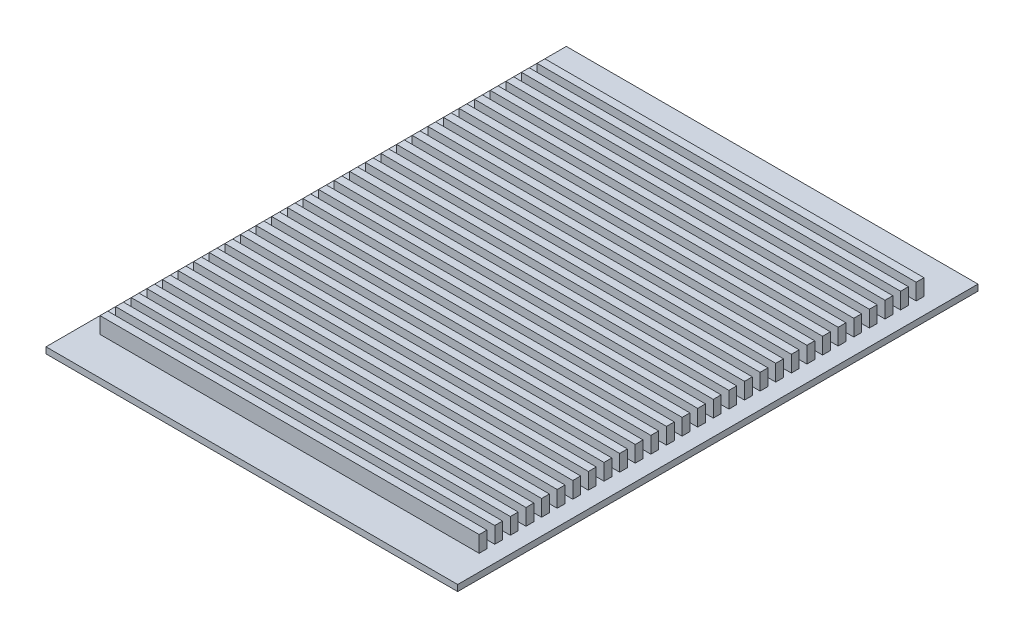
SolidWorks part; units mm, degrees
ref_plane "Front Plane" through (0, 0, 0) normal (0, 0, 1) x (1, 0, 0)
ref_plane "Top Plane" through (0, 0, 0) normal (0, 1, 0) x (1, 0, 0)
ref_plane "Right Plane" through (0, 0, 0) normal (1, 0, 0) x (0, 0, -1)
sketch "Sketch1" plane through (0, 0, 0) normal (0, 1, 0) x (1, 0, 0)
  line L1 (0, 0) -> (160.782, 0)
  line L2 (0, 0) -> (0, 203.2)
  line L3 (0, 203.2) -> (160.782, 203.2)
  line L4 (160.782, 0) -> (160.782, 203.2)
  dimension "D1" = 160.782
  dimension "D2" = 203.2
extrude "Boss-Extrude1" add sketch "Sketch1" along normal blind 2.413
sketch "Sketch2" plane through (0, 2.413, 0) normal (0, 1, 0) x (1, 0, 0)
  line L0 (0, 203.2) -> (0, 0) construction
  line L1 (6.35, 185.42) -> (154.432, 185.42) construction
  line L2 (6.35, 185.42) -> (6.35, 182.372) construction
  line L3 (6.35, 182.372) -> (154.432, 182.372) construction
  line L4 (154.432, 185.42) -> (154.432, 182.372) construction
  line L5 (160.782, 203.2) -> (0, 203.2) construction
  line L6 (6.35, 179.324) -> (6.35, 176.276) construction
  line L7 (6.35, 179.324) -> (154.432, 179.324) construction
  line L8 (154.432, 179.324) -> (154.432, 176.276) construction
  line L9 (6.35, 176.276) -> (154.432, 176.276) construction
  line L10 (6.35, 173.228) -> (6.35, 170.18) construction
  line L11 (6.35, 173.228) -> (154.432, 173.228) construction
  line L12 (154.432, 173.228) -> (154.432, 170.18) construction
  line L13 (6.35, 170.18) -> (154.432, 170.18) construction
  line L14 (6.35, 167.132) -> (6.35, 164.084) construction
  line L15 (6.35, 167.132) -> (154.432, 167.132) construction
  line L16 (154.432, 167.132) -> (154.432, 164.084) construction
  line L17 (6.35, 164.084) -> (154.432, 164.084) construction
  line L18 (6.35, 161.036) -> (6.35, 157.988) construction
  line L19 (6.35, 161.036) -> (154.432, 161.036) construction
  line L20 (154.432, 161.036) -> (154.432, 157.988) construction
  line L21 (6.35, 157.988) -> (154.432, 157.988) construction
  line L22 (6.35, 154.94) -> (6.35, 151.892) construction
  line L23 (6.35, 154.94) -> (154.432, 154.94) construction
  line L24 (154.432, 154.94) -> (154.432, 151.892) construction
  line L25 (6.35, 151.892) -> (154.432, 151.892) construction
  line L26 (6.35, 148.844) -> (6.35, 145.796) construction
  line L27 (6.35, 148.844) -> (154.432, 148.844) construction
  line L28 (154.432, 148.844) -> (154.432, 145.796) construction
  line L29 (6.35, 145.796) -> (154.432, 145.796) construction
  line L30 (6.35, 142.748) -> (6.35, 139.7) construction
  line L31 (6.35, 142.748) -> (154.432, 142.748) construction
  line L32 (154.432, 142.748) -> (154.432, 139.7) construction
  line L33 (6.35, 139.7) -> (154.432, 139.7) construction
  line L34 (6.35, 136.652) -> (6.35, 133.604) construction
  line L35 (6.35, 136.652) -> (154.432, 136.652) construction
  line L36 (154.432, 136.652) -> (154.432, 133.604) construction
  line L37 (6.35, 133.604) -> (154.432, 133.604) construction
  line L38 (6.35, 130.556) -> (6.35, 127.508) construction
  line L39 (6.35, 130.556) -> (154.432, 130.556) construction
  line L40 (154.432, 130.556) -> (154.432, 127.508) construction
  line L41 (6.35, 127.508) -> (154.432, 127.508) construction
  line L42 (6.35, 124.46) -> (6.35, 121.412) construction
  line L43 (6.35, 124.46) -> (154.432, 124.46) construction
  line L44 (154.432, 124.46) -> (154.432, 121.412) construction
  line L45 (6.35, 121.412) -> (154.432, 121.412) construction
  line L46 (6.35, 118.364) -> (6.35, 115.316) construction
  line L47 (6.35, 118.364) -> (154.432, 118.364) construction
  line L48 (154.432, 118.364) -> (154.432, 115.316) construction
  line L49 (6.35, 115.316) -> (154.432, 115.316) construction
  line L50 (6.35, 112.268) -> (6.35, 109.22) construction
  line L51 (6.35, 112.268) -> (154.432, 112.268) construction
  line L52 (154.432, 112.268) -> (154.432, 109.22) construction
  line L53 (6.35, 109.22) -> (154.432, 109.22) construction
  line L54 (6.35, 106.172) -> (6.35, 103.124) construction
  line L55 (6.35, 106.172) -> (154.432, 106.172) construction
  line L56 (154.432, 106.172) -> (154.432, 103.124) construction
  line L57 (6.35, 103.124) -> (154.432, 103.124) construction
  line L58 (6.35, 100.076) -> (6.35, 97.028) construction
  line L59 (6.35, 100.076) -> (154.432, 100.076) construction
  line L60 (154.432, 100.076) -> (154.432, 97.028) construction
  line L61 (6.35, 97.028) -> (154.432, 97.028) construction
  line L62 (6.35, 93.98) -> (6.35, 90.932) construction
  line L63 (6.35, 93.98) -> (154.432, 93.98) construction
  line L64 (154.432, 93.98) -> (154.432, 90.932) construction
  line L65 (6.35, 90.932) -> (154.432, 90.932) construction
  line L66 (6.35, 87.884) -> (6.35, 84.836) construction
  line L67 (6.35, 87.884) -> (154.432, 87.884) construction
  line L68 (154.432, 87.884) -> (154.432, 84.836) construction
  line L69 (6.35, 84.836) -> (154.432, 84.836) construction
  line L70 (6.35, 81.788) -> (6.35, 78.74) construction
  line L71 (6.35, 81.788) -> (154.432, 81.788) construction
  line L72 (154.432, 81.788) -> (154.432, 78.74) construction
  line L73 (6.35, 78.74) -> (154.432, 78.74) construction
  line L74 (6.35, 75.692) -> (6.35, 72.644) construction
  line L75 (6.35, 75.692) -> (154.432, 75.692) construction
  line L76 (154.432, 75.692) -> (154.432, 72.644) construction
  line L77 (6.35, 72.644) -> (154.432, 72.644) construction
  line L78 (6.35, 69.596) -> (6.35, 66.548) construction
  line L79 (6.35, 69.596) -> (154.432, 69.596) construction
  line L80 (154.432, 69.596) -> (154.432, 66.548) construction
  line L81 (6.35, 66.548) -> (154.432, 66.548) construction
  line L82 (6.35, 63.5) -> (6.35, 60.452) construction
  line L83 (6.35, 63.5) -> (154.432, 63.5) construction
  line L84 (154.432, 63.5) -> (154.432, 60.452) construction
  line L85 (6.35, 60.452) -> (154.432, 60.452) construction
  line L86 (6.35, 57.404) -> (6.35, 54.356) construction
  line L87 (6.35, 57.404) -> (154.432, 57.404) construction
  line L88 (154.432, 57.404) -> (154.432, 54.356) construction
  line L89 (6.35, 54.356) -> (154.432, 54.356) construction
  line L90 (6.35, 51.308) -> (6.35, 48.26) construction
  line L91 (6.35, 51.308) -> (154.432, 51.308) construction
  line L92 (154.432, 51.308) -> (154.432, 48.26) construction
  line L93 (6.35, 48.26) -> (154.432, 48.26) construction
  line L94 (6.35, 45.212) -> (6.35, 42.164) construction
  line L95 (6.35, 45.212) -> (154.432, 45.212) construction
  line L96 (154.432, 45.212) -> (154.432, 42.164) construction
  line L97 (6.35, 42.164) -> (154.432, 42.164) construction
  line L98 (6.35, 39.116) -> (6.35, 36.068) construction
  line L99 (6.35, 39.116) -> (154.432, 39.116) construction
  line L100 (154.432, 39.116) -> (154.432, 36.068) construction
  line L101 (6.35, 36.068) -> (154.432, 36.068) construction
  line L102 (6.35, 33.02) -> (6.35, 29.972) construction
  line L103 (6.35, 33.02) -> (154.432, 33.02) construction
  line L104 (154.432, 33.02) -> (154.432, 29.972) construction
  line L105 (6.35, 29.972) -> (154.432, 29.972) construction
  line L106 (6.35, 26.924) -> (6.35, 23.876) construction
  line L107 (6.35, 26.924) -> (154.432, 26.924) construction
  line L108 (154.432, 26.924) -> (154.432, 23.876) construction
  line L109 (6.35, 23.876) -> (154.432, 23.876) construction
  line L110 (6.35, 20.828) -> (6.35, 17.78) construction
  line L111 (6.35, 20.828) -> (154.432, 20.828) construction
  line L112 (154.432, 20.828) -> (154.432, 17.78) construction
  line L113 (6.35, 17.78) -> (154.432, 17.78) construction
  line L114 (6.35, 185.42) -> (6.35, 17.78) construction
  line L115 (6.35, 179.324) -> (6.35, 182.372)
  line L116 (6.35, 185.42) -> (154.432, 185.42)
  line L117 (6.35, 185.42) -> (6.35, 188.468)
  line L118 (6.35, 188.468) -> (154.432, 188.468)
  line L119 (154.432, 185.42) -> (154.432, 188.468)
  line L120 (6.35, 179.324) -> (154.432, 179.324)
  line L121 (154.432, 179.324) -> (154.432, 182.372)
  line L122 (6.35, 182.372) -> (154.432, 182.372)
  line L123 (6.35, 173.228) -> (6.35, 176.276)
  line L124 (6.35, 173.228) -> (154.432, 173.228)
  line L125 (154.432, 173.228) -> (154.432, 176.276)
  line L126 (6.35, 176.276) -> (154.432, 176.276)
  line L127 (6.35, 167.132) -> (6.35, 170.18)
  line L128 (6.35, 167.132) -> (154.432, 167.132)
  line L129 (154.432, 167.132) -> (154.432, 170.18)
  line L130 (6.35, 170.18) -> (154.432, 170.18)
  line L131 (6.35, 161.036) -> (6.35, 164.084)
  line L132 (6.35, 161.036) -> (154.432, 161.036)
  line L133 (154.432, 161.036) -> (154.432, 164.084)
  line L134 (6.35, 164.084) -> (154.432, 164.084)
  line L135 (6.35, 154.94) -> (6.35, 157.988)
  line L136 (6.35, 154.94) -> (154.432, 154.94)
  line L137 (154.432, 154.94) -> (154.432, 157.988)
  line L138 (6.35, 157.988) -> (154.432, 157.988)
  line L139 (6.35, 148.844) -> (6.35, 151.892)
  line L140 (6.35, 148.844) -> (154.432, 148.844)
  line L141 (154.432, 148.844) -> (154.432, 151.892)
  line L142 (6.35, 151.892) -> (154.432, 151.892)
  line L143 (6.35, 142.748) -> (6.35, 145.796)
  line L144 (6.35, 142.748) -> (154.432, 142.748)
  line L145 (154.432, 142.748) -> (154.432, 145.796)
  line L146 (6.35, 145.796) -> (154.432, 145.796)
  line L147 (6.35, 136.652) -> (6.35, 139.7)
  line L148 (6.35, 136.652) -> (154.432, 136.652)
  line L149 (154.432, 136.652) -> (154.432, 139.7)
  line L150 (6.35, 139.7) -> (154.432, 139.7)
  line L151 (6.35, 130.556) -> (6.35, 133.604)
  line L152 (6.35, 130.556) -> (154.432, 130.556)
  line L153 (154.432, 130.556) -> (154.432, 133.604)
  line L154 (6.35, 133.604) -> (154.432, 133.604)
  line L155 (6.35, 124.46) -> (6.35, 127.508)
  line L156 (6.35, 124.46) -> (154.432, 124.46)
  line L157 (154.432, 124.46) -> (154.432, 127.508)
  line L158 (6.35, 127.508) -> (154.432, 127.508)
  line L159 (6.35, 118.364) -> (6.35, 121.412)
  line L160 (6.35, 118.364) -> (154.432, 118.364)
  line L161 (154.432, 118.364) -> (154.432, 121.412)
  line L162 (6.35, 121.412) -> (154.432, 121.412)
  line L163 (6.35, 112.268) -> (6.35, 115.316)
  line L164 (6.35, 112.268) -> (154.432, 112.268)
  line L165 (154.432, 112.268) -> (154.432, 115.316)
  line L166 (6.35, 115.316) -> (154.432, 115.316)
  line L167 (6.35, 106.172) -> (6.35, 109.22)
  line L168 (6.35, 106.172) -> (154.432, 106.172)
  line L169 (154.432, 106.172) -> (154.432, 109.22)
  line L170 (6.35, 109.22) -> (154.432, 109.22)
  line L171 (6.35, 100.076) -> (6.35, 103.124)
  line L172 (6.35, 100.076) -> (154.432, 100.076)
  line L173 (154.432, 100.076) -> (154.432, 103.124)
  line L174 (6.35, 103.124) -> (154.432, 103.124)
  line L175 (6.35, 93.98) -> (6.35, 97.028)
  line L176 (6.35, 93.98) -> (154.432, 93.98)
  line L177 (154.432, 93.98) -> (154.432, 97.028)
  line L178 (6.35, 97.028) -> (154.432, 97.028)
  line L179 (6.35, 87.884) -> (6.35, 90.932)
  line L180 (6.35, 87.884) -> (154.432, 87.884)
  line L181 (154.432, 87.884) -> (154.432, 90.932)
  line L182 (6.35, 90.932) -> (154.432, 90.932)
  line L183 (6.35, 81.788) -> (6.35, 84.836)
  line L184 (6.35, 81.788) -> (154.432, 81.788)
  line L185 (154.432, 81.788) -> (154.432, 84.836)
  line L186 (6.35, 84.836) -> (154.432, 84.836)
  line L187 (6.35, 75.692) -> (6.35, 78.74)
  line L188 (6.35, 75.692) -> (154.432, 75.692)
  line L189 (154.432, 75.692) -> (154.432, 78.74)
  line L190 (6.35, 78.74) -> (154.432, 78.74)
  line L191 (6.35, 69.596) -> (6.35, 72.644)
  line L192 (6.35, 69.596) -> (154.432, 69.596)
  line L193 (154.432, 69.596) -> (154.432, 72.644)
  line L194 (6.35, 72.644) -> (154.432, 72.644)
  line L195 (6.35, 63.5) -> (6.35, 66.548)
  line L196 (6.35, 63.5) -> (154.432, 63.5)
  line L197 (154.432, 63.5) -> (154.432, 66.548)
  line L198 (6.35, 66.548) -> (154.432, 66.548)
  line L199 (6.35, 57.404) -> (6.35, 60.452)
  line L200 (6.35, 57.404) -> (154.432, 57.404)
  line L201 (154.432, 57.404) -> (154.432, 60.452)
  line L202 (6.35, 60.452) -> (154.432, 60.452)
  line L203 (6.35, 51.308) -> (6.35, 54.356)
  line L204 (6.35, 51.308) -> (154.432, 51.308)
  line L205 (154.432, 51.308) -> (154.432, 54.356)
  line L206 (6.35, 54.356) -> (154.432, 54.356)
  line L207 (6.35, 45.212) -> (6.35, 48.26)
  line L208 (6.35, 45.212) -> (154.432, 45.212)
  line L209 (154.432, 45.212) -> (154.432, 48.26)
  line L210 (6.35, 48.26) -> (154.432, 48.26)
  line L211 (6.35, 39.116) -> (6.35, 42.164)
  line L212 (6.35, 39.116) -> (154.432, 39.116)
  line L213 (154.432, 39.116) -> (154.432, 42.164)
  line L214 (6.35, 42.164) -> (154.432, 42.164)
  line L215 (6.35, 33.02) -> (6.35, 36.068)
  line L216 (6.35, 33.02) -> (154.432, 33.02)
  line L217 (154.432, 33.02) -> (154.432, 36.068)
  line L218 (6.35, 36.068) -> (154.432, 36.068)
  line L219 (6.35, 26.924) -> (6.35, 29.972)
  line L220 (6.35, 26.924) -> (154.432, 26.924)
  line L221 (154.432, 26.924) -> (154.432, 29.972)
  line L222 (6.35, 29.972) -> (154.432, 29.972)
  line L223 (6.35, 20.828) -> (6.35, 23.876)
  line L224 (6.35, 20.828) -> (154.432, 20.828)
  line L225 (154.432, 20.828) -> (154.432, 23.876)
  line L226 (6.35, 23.876) -> (154.432, 23.876)
  line L227 (6.35, 14.732) -> (6.35, 17.78)
  line L228 (6.35, 14.732) -> (154.432, 14.732)
  line L229 (154.432, 14.732) -> (154.432, 17.78)
  line L230 (6.35, 17.78) -> (154.432, 17.78)
  point P8 (80.391, 203.2)
  point P9 (80.391, 185.42)
  point P10 (0, 101.6)
  point P11 (6.35, 101.6)
  dimension "D1" = 6.35
  dimension "D2" = 3.048
  dimension "D4" = 3.048
  dimension "D5" = 3.048
  dimension "D6" = 29
  dimension "D3" = 28
extrude "Boss-Extrude2" add sketch "Sketch2" along normal blind 6.35
